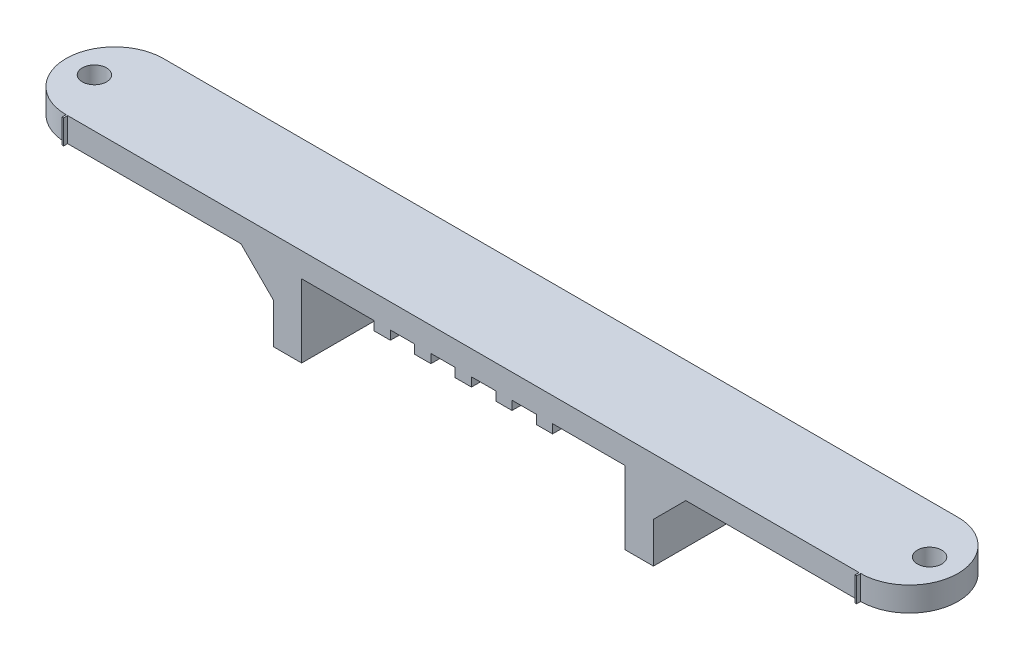
SolidWorks part; units mm, degrees
ref_plane "Front Plane" through (0, 0, 0) normal (0, 0, 1) x (1, 0, 0)
ref_plane "Top Plane" through (0, 0, 0) normal (0, 1, 0) x (1, 0, 0)
ref_plane "Right Plane" through (0, 0, 0) normal (1, 0, 0) x (0, 0, -1)
sketch "Sketch1" plane through (0, 0, 0) normal (0, 1, 0) x (1, 0, 0)
  line L0 (-49, 0) -> (49, 0) construction
  line L1 (-49, 6) -> (49, 6)
  line L2 (-49, -6) -> (49, -6)
  arc A0 (-49, 6) -> (-49, -6) centre (-49, 0) ccw
  arc A1 (49, -6) -> (49, 6) centre (49, 0) ccw
  circle A2 centre (-51.5, 0) radius 1.5
  circle A3 centre (51.5, 0) radius 1.5
  point P2 (0, 0)
  point P12 (-55, 0)
  point P13 (55, 0)
  dimension "D3" = 3
  dimension "D4" = 3.5
  dimension "D1" = 110
  dimension "D2" = 12
  dimension "D5" = 3.5
extrude "Boss-Extrude1" add sketch "Sketch1" along normal blind 3 contours L2 A1 L1 A0 | A2 | A3
sketch "Sketch4" plane through (0, 0, 0) normal (0, -1, 0) x (1, 0, 0)
  line L0 (-19.94, 6) -> (-19.94, -6)
  line L1 (-49, 6) -> (49, 6) construction
  line L2 (-49, -6) -> (49, -6) construction
  line L3 (-19.94, -6) -> (-23.44, -6)
  line L4 (-23.44, -6) -> (-23.44, 6)
  line L5 (-23.44, 6) -> (-19.94, 6)
  line L6 (0, 6) -> (0, -6) construction
  line L7 (-19.94, 5.075) -> (-19.94, -14.3256) construction
  line L8 (23.44, -6) -> (23.44, 6)
  line L9 (19.94, -6) -> (23.44, -6)
  line L10 (19.94, 6) -> (19.94, -6)
  line L11 (23.44, 6) -> (19.94, 6)
  dimension "D1" = 0
  dimension "D2" = 3.5
extrude "Boss-Extrude3" add sketch "Sketch4" along normal blind 9
sketch "Sketch5" plane through (0, 0, 0) normal (0, -1, 0) x (1, 0, 0)
  line L1 (4, 6) -> (4, -6)
  line L2 (4, 6) -> (6, 6)
  line L6 (-19.94, -6) -> (19.94, -6) construction
  line L7 (-1, 6) -> (1, 6)
  line L8 (-1, 6) -> (-1, -6)
  line L9 (-1, -6) -> (1, -6)
  line L10 (1, 6) -> (1, -6)
  line L11 (-1, 6) -> (1, -6) construction
  line L12 (-1, -6) -> (1, 6) construction
  line L13 (6, 6) -> (6, -6)
  line L14 (4, -6) -> (6, -6)
  line L15 (9, 6) -> (9, -6)
  line L16 (9, 6) -> (11, 6)
  line L17 (11, 6) -> (11, -6)
  line L18 (9, -6) -> (11, -6)
  line L19 (-4, 6) -> (-4, -6)
  line L20 (-6, -6) -> (-4, -6)
  line L21 (-6, 6) -> (-6, -6)
  line L22 (-6, 6) -> (-4, 6)
  line L23 (-9, 6) -> (-9, -6)
  line L24 (-11, -6) -> (-9, -6)
  line L25 (-11, 6) -> (-11, -6)
  line L26 (-11, 6) -> (-9, 6)
  point P0 (0, 0)
  dimension "D1" = 2
  dimension "D2" = 3
  dimension "D3" = 3
extrude "Boss-Extrude4" add sketch "Sketch5" along normal blind 1.1
sketch "Sketch6" plane through (0, 0, 6) normal (0, 0, 1) x (1, 0, 0)
  line L0 (49, 0) -> (49, 3)
  line L1 (49, 3) -> (48.8, 3)
  line L2 (-49, 3) -> (49, 3) construction
  line L3 (48.8, 3) -> (48.8, 0)
  line L4 (23.44, 0) -> (49, 0) construction
  line L5 (48.8, 0) -> (49, 0)
  line L6 (0, 0) -> (0, 3) construction
  line L7 (-48.8, 0) -> (-49, 0)
  line L8 (-48.8, 3) -> (-48.8, 0)
  line L9 (-49, 3) -> (-48.8, 3)
  line L10 (-49, 0) -> (-49, 3)
  dimension "D1" = 0.2
extrude "Boss-Extrude5" add sketch "Sketch6" along normal blind 0.5 contours L0 L1 L3 L5 | L8 L7 L10 L9
chamfer "Chamfer1" distance 4 2 edges at (-23.44, 0, 0) (23.44, 0, 0)
